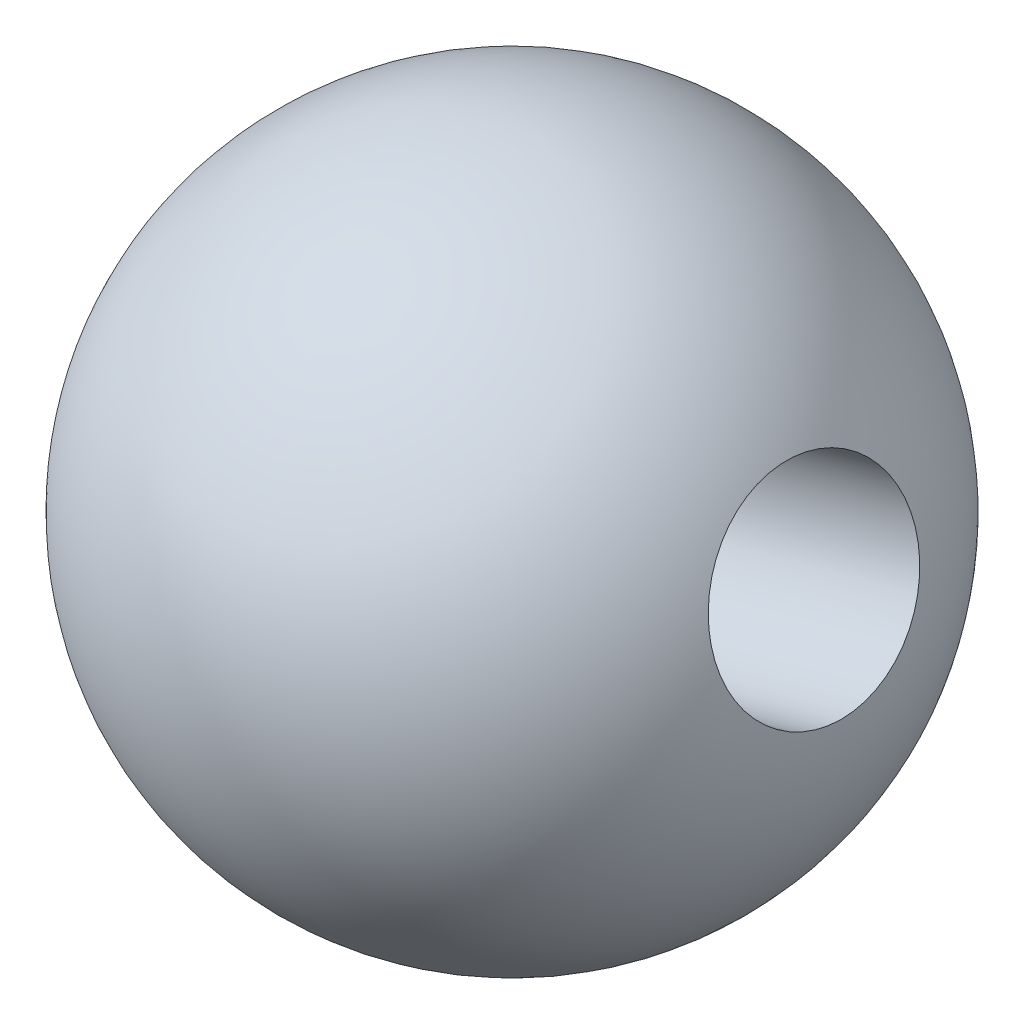
SolidWorks part; units mm, degrees
ref_plane "Front Plane" through (0, 0, 0) normal (0, 0, 1) x (1, 0, 0)
ref_plane "Top Plane" through (0, 0, 0) normal (0, 1, 0) x (1, 0, 0)
ref_plane "Right Plane" through (0, 0, 0) normal (1, 0, 0) x (0, 0, -1)
sketch "Sketch1" plane through (-81.3211, -22.5088, 0) normal (-0.9638, -0.2668, 0) x (0, 0, 1)
  line L0 (44.795, -3.5215) -> (44.795, -23.5215)
  arc A0 (44.795, -3.5215) -> (44.795, -23.5215) centre (44.795, -13.5215) cw
  dimension "D1" = 10
revolve "Revolve1" add sketch "Sketch1" angle 360 about L0
sketch "Sketch2" plane through (-81.3211, -22.5088, 0) normal (-0.9638, -0.2668, 0) x (0, 0, 1)
  circle A0 centre (44.795, -13.5215) radius 3.1
  dimension "D1" = 6.2
extrude "Cut-Extrude1" cut sketch "Sketch2" against normal through all
